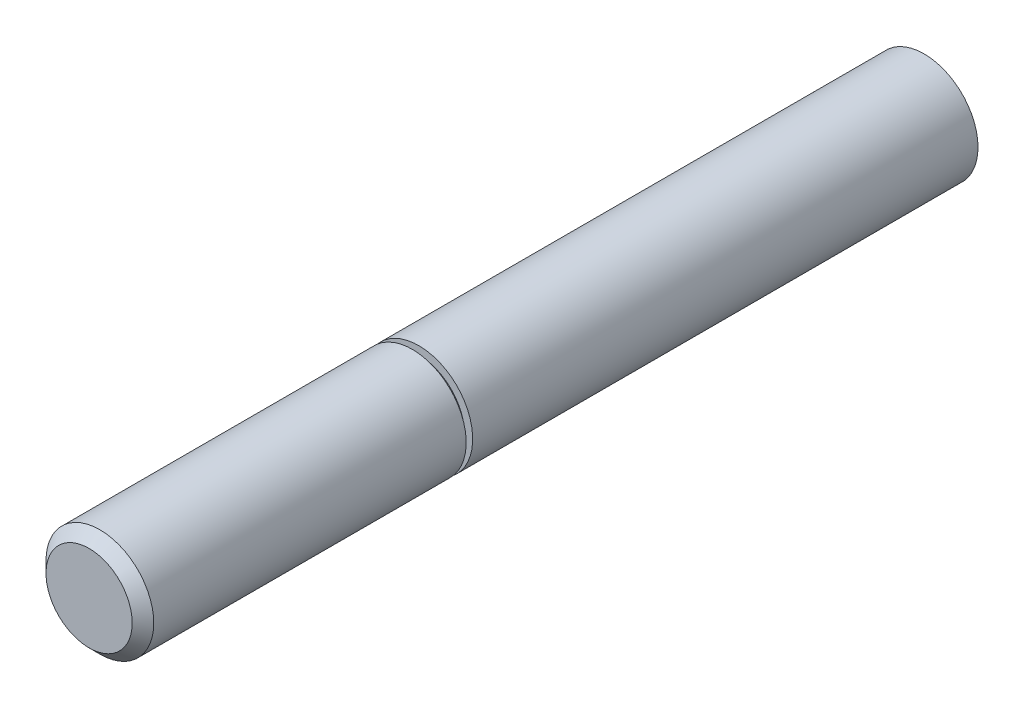
SolidWorks part; units mm, degrees
material "2014-T4"
ref_plane "Płaszczyzna przednia" through (0, 0, 0) normal (0, 0, 1) x (1, 0, 0)
ref_plane "Płaszczyzna górna" through (0, 0, 0) normal (0, 1, 0) x (1, 0, 0)
ref_plane "Płaszczyzna prawa" through (0, 0, 0) normal (1, 0, 0) x (0, 0, -1)
sketch "Szkic1" plane through (0, 0, 0) normal (0, 0, 1) x (1, 0, 0)
  circle A0 centre (0, 0) radius 10
  dimension "D1" = 20
extrude "Dodanie-wyciągnięcie1" add sketch "Szkic1" along normal blind 155
chamfer "Sfazowanie2" distance 2 angle 45 1 edges at (10, 0, 155)
sketch "Szkic2" plane through (0, 0, 0) normal (0, 1, 0) x (1, 0, 0)
  line L2 (10, 0) -> (10, -153)
  line L3 (10, 0) -> (10, -153)
  line L6 (-10, -153) -> (-10, 0)
  line L7 (-10, -153) -> (-10, 0)
  line L8 (10, -95) -> (8.5, -95)
  line L9 (8.5, -95) -> (8.5, -93.8)
  line L10 (8.5, -93.8) -> (10, -93.8)
  line L11 (0, 0) -> (0, -174.8314) construction
  line L12 (10, -93.8) -> (10, -95)
  line L18 (-10, 0) -> (10, 0)
  line L20 (10, -153) -> (8, -155)
  line L21 (8, -155) -> (-8, -155)
  line L22 (10, -153) -> (8, -155)
  line L23 (8, -155) -> (-8, -155)
  line L24 (-8, -155) -> (-10, -153)
  line L25 (-8, -155) -> (-10, -153)
  line L28 (-10, 0) -> (10, 0)
  dimension "D1" = 1.5
  dimension "D2" = 1.2
  dimension "D3" = 60
revolve "Wycięcie-obrót1" cut sketch "Szkic2" angle 360 about L11
